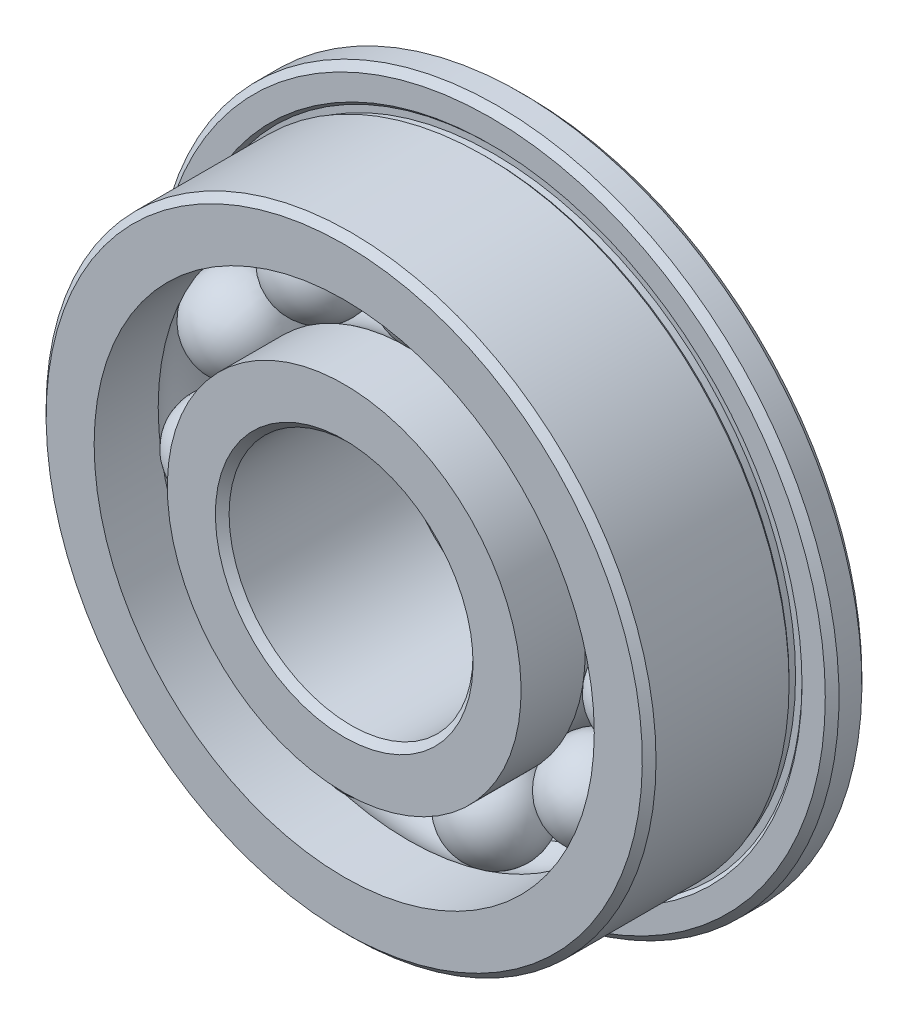
SolidWorks part; units mm, degrees
ref_plane "Front Plane" through (0, 0, 0) normal (0, 0, 1) x (1, 0, 0)
ref_plane "Top Plane" through (0, 0, 0) normal (0, 1, 0) x (1, 0, 0)
ref_plane "Right Plane" through (0, 0, 0) normal (1, 0, 0) x (0, 0, -1)
sketch "Sketch1" plane through (0, 0, 0) normal (1, 0, 0) x (0, 0, -1)
  line L0 (0, 5) -> (0, -5) construction
  line L1 (-1.5, 5) -> (1.5, 5) construction
  line L2 (0, 0) -> (1.5, 0) construction
  line L3 (1.5, 5.6) -> (1.5, -5.6) construction
  line L4 (1.5, -5.6) -> (0.9, -5.6) construction
  line L5 (1.5, 2) -> (0, 2) construction
  line L6 (1.5, 2) -> (1.5, -2) construction
  dimension "OD" = 10
  dimension "Width" = 3
  dimension "Flange Thickness" = 0.6
  dimension "ID" = 4
  dimension "Flange OD" = 11.2
sketch "Sketch2" plane through (0, 0, 0) normal (1, 0, 0) x (0, 0, -1)
  line L0 (1.5, 5.6) -> (0.9, 5.6)
  line L1 (0.9, 5.6) -> (0.9, 5.1061)
  line L2 (0.7939, 5) -> (-1.5, 5)
  line L3 (-1.5, 5) -> (-1.5, 4.1)
  line L4 (-1.5, 4.1) -> (-0.45, 4.1)
  line L5 (1.5, 5.6) -> (1.5, -5.6) construction
  line L6 (1.5, 4.1) -> (1.5, 5.6)
  line L7 (1.5, 2) -> (-1.5, 2)
  line L8 (-1.5, 2) -> (-1.5, 2.9)
  line L9 (-1.5, 2.9) -> (-0.45, 2.9)
  line L10 (1.5, 2.9) -> (1.5, 2)
  line L11 (0, 5) -> (0, 2) construction
  line L12 (-0.75, 3.5) -> (0.75, 3.5) construction
  line L13 (0.45, 4.1) -> (1.5, 4.1)
  line L14 (0.45, 2.9) -> (1.5, 2.9)
  line L15 (0.9, 5.1061) -> (0.953, 5.053)
  line L16 (0.953, 5.053) -> (0.953, 4.947)
  line L17 (0.953, 4.947) -> (0.847, 4.947)
  line L18 (0.847, 4.947) -> (0.7939, 5)
  line L19 (0.9, 5) -> (0.953, 4.947) construction
  line L20 (0.953, 5.053) -> (0.847, 4.947) construction
  line L21 (0.7939, 5) -> (0.9, 5) construction
  line L22 (0.9, 5) -> (0.9, 5.1061) construction
  circle A0 centre (0, 3.5) radius 0.75 construction
  arc A1 (-0.45, 4.1) -> (0.45, 4.1) centre (0, 3.5) cw
  arc A2 (-0.45, 2.9) -> (0.45, 2.9) centre (0, 3.5) ccw
  dimension "D1" = 3
  dimension "Ball Dia." = 1.5
  dimension "D2" = 135
  dimension "D3" = 0.15
  dimension "D4" = 1.2
  dimension "Race Thikness" = 0.9
revolve "Revolve1" add sketch "Sketch2" angle 360 about L2
fillet "Fillet1" radius 0.1125 3 edges at (0, -5.6, -1.5) (0, -5.6, -0.9) (0, -5, 1.5) profile chamfer
sketch "Sketch3" plane through (0, 0, 0) normal (0, 0, 1) x (1, 0, 0)
  line L0 (-2, 0) -> (2, 0) construction
  line L1 (-5, 0) -> (5, 0) construction
  point P5 (0, 0)
  dimension "ID2" = 4
  dimension "OD2" = 10
fillet "Fillet2" radius 0.1125 2 edges at (0, -2, -1.5) (0, -2, 1.5) profile chamfer
sketch "Sketch7" plane through (0, 0, 0) normal (0, 0, 1) x (1, 0, 0)
  line L0 (0, 4.25) -> (0, 2.75)
  line L1 (0, 5.6) -> (0, -5.6) construction
  line L2 (-0.9324, 4.25) -> (0, 0) construction
  line L3 (0, 0) -> (0.9324, 4.25) construction
  line L4 (0.9324, 4.25) -> (-0.9324, 4.25) construction
  circle A0 centre (0, 3.5) radius 0.75 construction
  circle A1 centre (0, 0) radius 4.25 construction
  circle A2 centre (0, 0) radius 2.75 construction
  arc A4 (0, 4.25) -> (0, 2.75) centre (0, 3.5) ccw
  dimension "D1" = 24.747
revolve "Revolve3" add sketch "Sketch7" angle 360 about L0
pattern_circular "CirPattern3" count 11 over 360 about axis through (0, 0, 0) along (0, 0, 1) of bodies 107
sketch "Sketch8" plane through (0, 0, 0) normal (1, 0, 0) x (0, 0, -1)
  line L0 (-1.5, 5) -> (1.5, 5) construction
  line L1 (1.5, 5) -> (1.5, 5.6) construction
  line L2 (-1.5, -5) -> (1.5, -5) construction
  line L3 (1.5, 5.6) -> (1.5, -5.6) construction
  dimension "D1" = 10
equation "\"Ball Dia.@Sketch2\" = ( \"OD@Sketch1\" - \"ID@Sketch1\" ) * .25"
equation "\"D3@Sketch2\"=\"Flange Thickness@Sketch1\"/4"
equation "\"D1@Fillet1\" = \"Race Thikness@Sketch2\" / 8"
equation "\"ID2@Sketch3\" = \"ID@Sketch1\""
equation "\"OD2@Sketch3\" = \"OD@Sketch1\""
equation "\"D1@Fillet2\" = \"Race Thikness@Sketch2\" / 8"
equation "\"D1@CirPattern3\"=360/\"D1@Sketch7\"-4"
equation "\"D4@Sketch2\" = ( \"OD@Sketch1\" - \"ID@Sketch1\" ) * .2"
